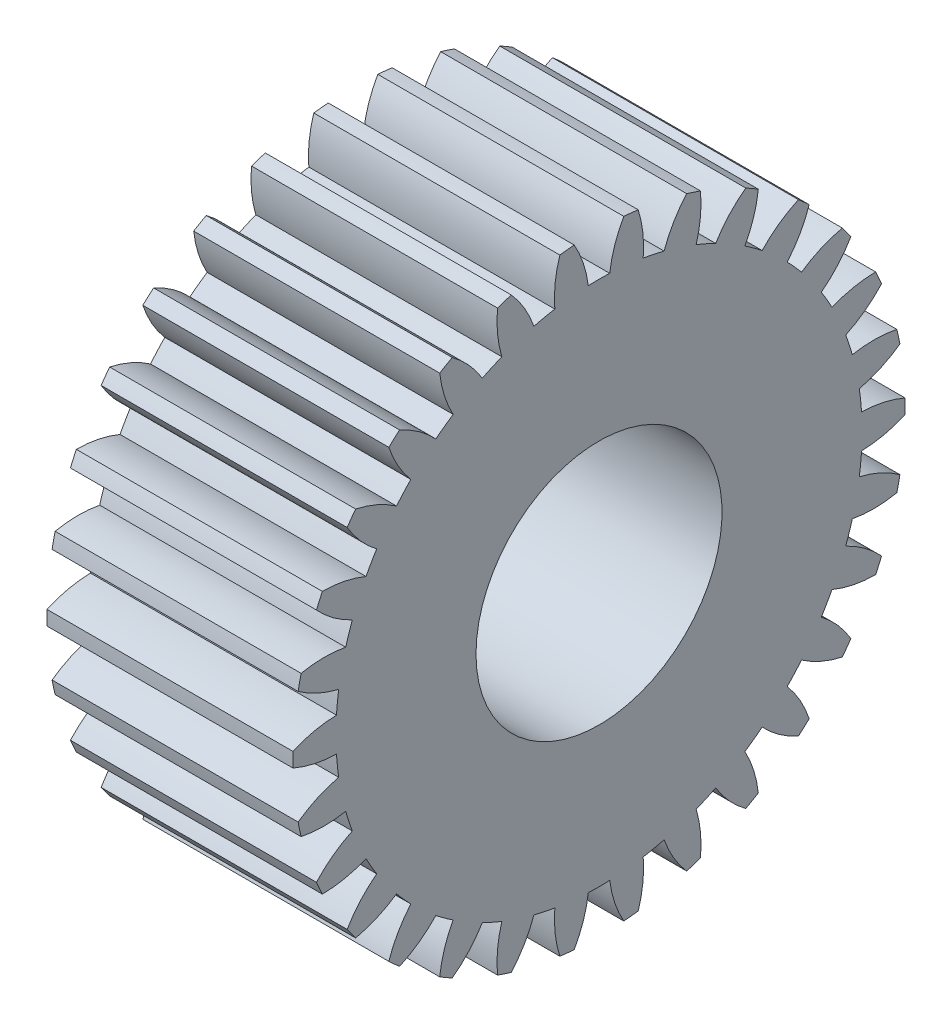
SolidWorks part; units mm, degrees
ref_plane "Plane1" through (0, 0, 0) normal (0, 0, 1) x (1, 0, 0)
ref_plane "Plane2" through (0, 0, 0) normal (0, 1, 0) x (1, 0, 0)
ref_plane "Plane3" through (0, 0, 0) normal (1, 0, 0) x (0, 0, -1)
sketch "HoldingSke" plane through (0, 0, 0) normal (0, 1, 0) x (1, 0, 0)
  line L0 (0, 0) -> (1.2372, -0.7143)
  line L1 (-15, 0) -> (100, 0) construction
  line L2 (0, 0) -> (-2.1039, 2.3779)
  line L3 (0, 0) -> (-11.863, 4.5341)
  line L4 (0, 0) -> (7.479, 4.318)
  line L5 (0, 0) -> (-46.8476, -17.4728)
  line L6 (0, 0) -> (-7.4607, -5.0337)
  line L7 (-2.1039, 2.3779) -> (8.6586, 51.2059)
  line L8 (-76.2, 54.61) -> (-76.1, 54.61)
  line L9 (-67.7845, 28.3722) -> (-49.3413, 33.142)
  line L10 (-76.2, 71.12) -> (104.1128, 71.12)
  line L11 (0, 0) -> (-9, 0)
  line L12 (-76.2, 101.6) -> (-76.173, 101.6)
  line L13 (24.9733, 27.94) -> (52.9518, 28.4284)
  line L14 (24.9733, 27.94) -> (24.9743, 27.94)
  line L15 (24.9733, 27.94) -> (100.4006, 29.5858)
  line L16 (-63.627, -0.7) -> (-12.827, -0.7)
  circle A0 centre (0, 0) radius 0.5
  circle A1 centre (0, 0) radius 9.624
  circle A2 centre (0, 0) radius 37.5
  circle A3 centre (0, 0) radius 0.5
  dimension "MHD" = 19.248
  dimension "Hub_dia" = 75
  dimension "Bore" = 1
  dimension "MBD" = 1
  dimension "Num_teeth" = 30
  dimension "Pitch" = 1.4286
  dimension "Overall_len" = 50
  dimension "Show_teeth" = 30
  dimension "Thickness" = 9
  dimension "OAL" = 50.0001
  dimension "T_dim" = 0.1
  dimension "Ap" = 14.5
  dimension "H" = 19.05
  dimension "Pitch_radius" = 180.3128
  dimension "Width" = 9
  dimension "Backlash" = 0.027
  dimension "Addendum_fac" = 1
  dimension "Dedendum_fac" = 1.25
  dimension "Clearance_fac" = 0.25
  dimension "Dedendum_add" = 0.001
  dimension "Module" = 0.7
sketch "BasProSke" plane through (0, 0, 0) normal (0, 1, 0) x (1, 0, 0)
  line L0 (-10, 0) -> (60, 0) construction
  line L1 (0, 0) -> (0, 11.2)
  line L2 (0, 0) -> (9, 0)
  line L3 (9, 0) -> (9, 11.2)
  line L4 (9, 11.2) -> (0, 11.2)
  dimension "Thickness" = 9
  dimension "Diameter" = 22.4
revolve "Base-Revolve" add sketch "BasProSke" angle 360 about L0
sketch "TooCutSke" plane through (0, 0, 0) normal (1, 0, 0) x (0, 0, -1)
  line L1 (0, 0) -> (0, 107) construction
  line L2 (0, 0) -> (-0.5968, 10.483) construction
  line L3 (0, 0) -> (-2.1926, 20.8611) construction
  line L4 (-0.5968, 10.483) -> (-1.0963, 10.4305) construction
  arc A0 (0.3913, 9.616) -> (-0.3913, 9.616) centre (0, 0) ccw
  arc A1 (0.9211, 11.1875) -> (-0.9211, 11.1875) centre (0, 0) ccw
  circle A2 centre (0, 0) radius 10.5 construction
  circle A3 centre (0, 0) radius 10.1656 construction
  arc A4 (-0.3913, 9.616) -> (-0.9211, 11.1875) centre (-4.5578, 9.0865) ccw
  arc A5 (0.9211, 11.1875) -> (0.3913, 9.616) centre (4.5578, 9.0865) ccw
  dimension "Root_dia" = 19.248
  dimension "Overcut_dia" = 22.4508
  dimension "Pitch_dia" = 21
  dimension "Base_dia" = 20.3311
  dimension "Flank_rad" = 4.2
  dimension "Half_ang" = 6
  dimension "Half_CT" = 0.5023
extrude "ToothCut" cut sketch "TooCutSke" along normal through all
fillet "Breaks" [suppressed] radius 0.014
fillet "RootFillets" [suppressed] radius 0.176
pattern_circular "TeethCuts" count 30 every 12 about axis through (-10, 0, 0) along (1, 0, 0) of "ToothCut", "RootFillets", "Breaks"
sketch "HubNeaOneSke" plane through (0, 0, 0) normal (-1, 0, 0) x (0, 0, 1)
  circle A0 centre (0, 0) radius 9.624
  dimension "Diameter" = 19.248
extrude "HubNearOne" [suppressed] add sketch "HubNeaOneSke" along normal blind 41.0001
sketch "HubNeaBotSke" plane through (0, 0, 0) normal (-1, 0, 0) x (0, 0, 1)
  circle A0 centre (0, 0) radius 9.624
  dimension "Diameter" = 19.248
extrude "HubNearBoth" [suppressed] add sketch "HubNeaBotSke" along normal blind 20.5
ref_plane "FarPln" through (9, 0, 0) normal (1, 0, 0) x (0, 0, -1)
sketch "HubFarSke" plane through (9, 0, 0) normal (1, 0, 0) x (0, 0, -1)
  circle A0 centre (0, 0) radius 9.624
  dimension "Diameter" = 19.248
extrude "HubFar" [suppressed] add sketch "HubFarSke" along normal blind 20.5
sketch "BorSke" plane through (0, 0, 0) normal (1, 0, 0) x (0, 0, -1)
  circle A0 centre (0, 0) radius 4.5
  dimension "Diameter" = 9
extrude "Bore" cut sketch "BorSke" along normal mid plane 100.0001
sketch "KeySke" plane through (0, 0, 0) normal (1, 0, 0) x (0, 0, -1)
  line L0 (-0.05, 0) -> (-0.05, 0.6)
  line L1 (-0.05, 0.6) -> (0.05, 0.6)
  line L2 (0.05, 0.6) -> (0.05, 0)
  line L3 (0, 0) -> (0, 34) construction
  line L4 (-0.05, 0) -> (0.05, 0)
  dimension "Offset" = 0.6
  dimension "Width" = 0.1
extrude "Keyway" [suppressed] cut sketch "KeySke" along normal mid plane 100.0001
pattern_circular "Keyway2" [suppressed] count 2 every 90 about axis through (-10, 0, 0) along (1, 0, 0)
equation "' \"Module@HoldingSke\" = 6.35"
equation "' \"Num_teeth@HoldingSke\" = 12"
equation "' \"Ap@HoldingSke\" =  20"
equation "' \"Ap@HoldingSke\" = 20"
equation "' \"Width@HoldingSke\" = 0.5 * 25.4"
equation "' \"Hub_dia@HoldingSke\"= 1 * 25.4"
equation "' \"Hub_dia@HoldingSke\" = 1 * 25.4"
equation "' \"Overall_len@HoldingSke\" = 1.0 * 25.4"
equation "' \"Bore@HoldingSke\" = 0.75 * 25.4"
equation "' \"T_dim@HoldingSke\" = 0.1 * 25.4"
equation "' \"Width@KeySke\" = 0.25 * 25.4"
equation "' \"Show_teeth@HoldingSke\" = 13"
equation "' \"Backlash@HoldingSke\" = 0.009 * 25.4"
equation "' \"Addendum_fac@HoldingSke\" = 1.0"
equation "' \"Dedendum_fac@HoldingSke\" = 1.25"
equation "' \"Dedendum_add@HoldingSke\" = 0.00005 * 25.4"
equation "' \"Clearance_fac@HoldingSke\" = 0.25"
equation "\"Pitch@HoldingSke\" = 1 / \"Module@HoldingSke\""
equation "\"Overcut_dia@TooCutSke\" = (\"Num_teeth@HoldingSke\" + 2 * \"Addendum_fac@HoldingSke\") / \"Pitch@HoldingSke\" + 0.002 * 25.4"
equation "\"Pitch_dia@TooCutSke\" = \"Num_teeth@HoldingSke\" / \"Pitch@HoldingSke\""
equation "\"Base_dia@TooCutSke\" = \"Num_teeth@HoldingSke\" / \"Pitch@HoldingSke\" * cos((\"Ap@HoldingSke\"  * 3.14159265 / 180))"
equation "\"Root_dia@TooCutSke\" = (\"Num_teeth@HoldingSke\" + 2) / \"Pitch@HoldingSke\" - 2 * (\"Addendum_fac@HoldingSke\" + \"Dedendum_fac@HoldingSke\") / \"Pitch@HoldingSke\" - \"Dedendum_add@HoldingSke\" * 2"
equation "\"Half_ang@TooCutSke\" = 180 / \"Num_teeth@HoldingSke\""
equation "\"Half_CT@TooCutSke\" = \"Num_teeth@HoldingSke\" / \"Pitch@HoldingSke\" * sin((3.14159265 / 2 / \"Num_teeth@HoldingSke\")) / 2 - 7 * \"Backlash@HoldingSke\" / 4"
equation "\"Flank_rad@TooCutSke\" = \"Num_teeth@HoldingSke\" / \"Pitch@HoldingSke\" / 5"
equation "\"Radius@RootFillets\" = \"Clearance_fac@HoldingSke\" / \"Pitch@HoldingSke\" + \"Dedendum_add@HoldingSke\""
equation "\"Break_rad@Breaks\" = 0.02 / \"Pitch@HoldingSke\""
equation "\"Thickness@HoldingSke\" = \"Width@HoldingSke\""
equation "\"OAL@HoldingSke\" = \"Thickness@HoldingSke\""
equation "\"MHD@HoldingSke\" = (\"Num_teeth@HoldingSke\" + 2) / \"Pitch@HoldingSke\" - 2 * (\"Addendum_fac@HoldingSke\" + \"Dedendum_fac@HoldingSke\")  / \"Pitch@HoldingSke\" - \"Dedendum_add@HoldingSke\" * 2"
equation "\"MBD@HoldingSke\" = (\"Num_teeth@HoldingSke\" + 2) / \"Pitch@HoldingSke\" - 2 * (\"Addendum_fac@HoldingSke\" + \"Dedendum_fac@HoldingSke\")  / \"Pitch@HoldingSke\" - \"Dedendum_add@HoldingSke\" * 2 - 0.002 * 25.4"
equation "\"MHD@HoldingSke\" = ((sgn( \"MHD@HoldingSke\" - \"Hub_dia@HoldingSke\" )-1)*( \"MHD@HoldingSke\" - \"Hub_dia@HoldingSke\" ))/-2+ \"Hub_dia@HoldingSke\""
equation "\"MBD@HoldingSke\" = ((sgn( \"MBD@HoldingSke\" - \"Bore@HoldingSke\" )-1)*( \"MBD@HoldingSke\" - \"Bore@HoldingSke\" ))/-2+ \"Bore@HoldingSke\""
equation "\"OAL@HoldingSke\" = ((sgn( \"OAL@HoldingSke\" - \"Overall_len@HoldingSke\" )+1)*( \"OAL@HoldingSke\" - \"Overall_len@HoldingSke\" ))/2 + \"Overall_len@HoldingSke\" + 0.000002 * 25.4"
equation "\"Num_teeth@TeethCuts\" = int( \"Show_teeth@HoldingSke\" ) + 1"
equation "\"Num_teeth@TeethCuts\" = ((sgn( \"Num_teeth@TeethCuts\" - \"Num_teeth@HoldingSke\" )-1)*( \"Num_teeth@TeethCuts\" - \"Num_teeth@HoldingSke\" ))/-2+ \"Num_teeth@HoldingSke\""
equation "\"Num_teeth@TeethCuts\" = ((sgn( \"Num_teeth@TeethCuts\" - 2.0)+1)*( \"Num_teeth@TeethCuts\" - 2.0))/2 +2.0"
equation "\"Angle@TeethCuts\" = 360.0 / \"Num_teeth@HoldingSke\""
equation "\"Diameter@BasProSke\" = (\"Num_teeth@HoldingSke\" + 2 * \"Addendum_fac@HoldingSke\") / \"Pitch@HoldingSke\""
equation "\"Thickness@BasProSke\"  = \"Thickness@HoldingSke\""
equation "' \"Fillet_rad@BasProSke\" =  \"Thickness@HoldingSke\" * 0.05"
equation "' \"Fillet_rad@BasProSke\" = \"Thickness@HoldingSke\" * 0.05"
equation "\"MHD@HoldingSke\" = ((sgn( \"MHD@HoldingSke\" - \"Root_dia@TooCutSke\" )-1)*( \"MHD@HoldingSke\" - \"Root_dia@TooCutSke\" ))/-2+ \"Root_dia@TooCutSke\""
equation "\"Diameter@HubNeaOneSke\" = \"MHD@HoldingSke\""
equation "\"Length@HubNearOne\" = \"OAL@HoldingSke\" - \"Thickness@BasProSke\""
equation "\"Diameter@HubNeaBotSke\" = \"MHD@HoldingSke\""
equation "\"Length@HubNearBoth\" = ( \"OAL@HoldingSke\" - \"Thickness@BasProSke\" ) / 2.0"
equation "\"Thickness@FarPln\" = \"Thickness@BasProSke\""
equation "\"Diameter@HubFarSke\" = \"MHD@HoldingSke\""
equation "\"Length@HubFar\" = ( \"OAL@HoldingSke\" - \"Thickness@BasProSke\" ) / 2.0"
equation "\"Diameter@BorSke\"=9"
equation "\"D1@Bore\" = \"OAL@HoldingSke\" * 2.0"
equation "\"D1@Keyway\" = \"OAL@HoldingSke\" * 2.0"
equation "\"Offset@KeySke\" = \"T_dim@HoldingSke\" + \"MBD@HoldingSke\" / 2.0"
